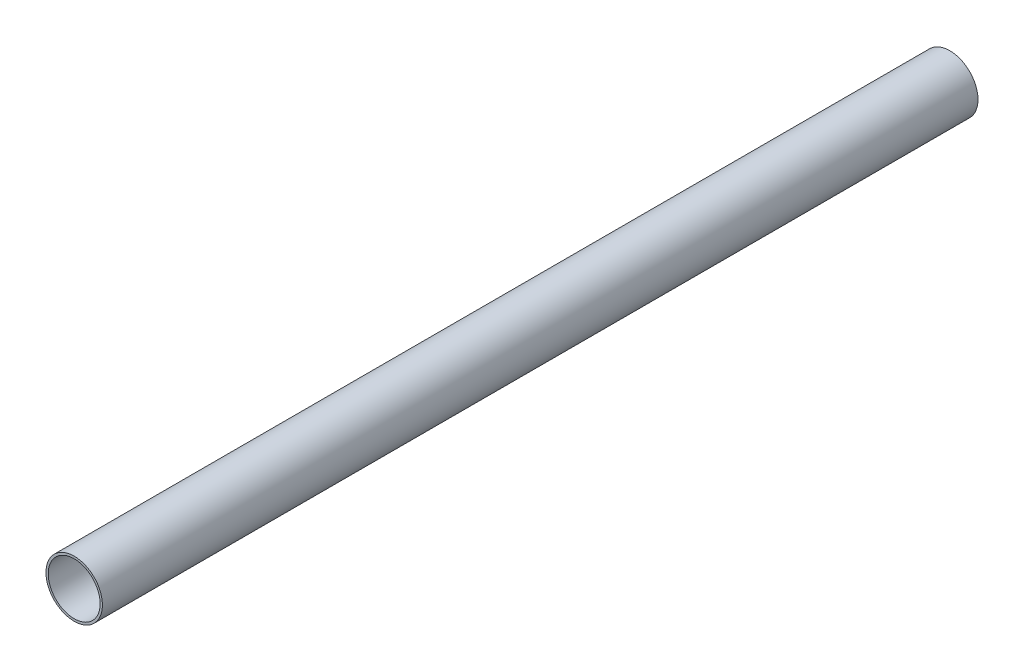
SolidWorks part; units mm, degrees
material "PC High Viscosity"
ref_plane "Front Plane" through (0, 0, 0) normal (0, 0, 1) x (1, 0, 0)
ref_plane "Top Plane" through (0, 0, 0) normal (0, 1, 0) x (1, 0, 0)
ref_plane "Right Plane" through (0, 0, 0) normal (1, 0, 0) x (0, 0, -1)
sketch "Sketch1" plane through (0, 0, 0) normal (0, 0, 1) x (1, 0, 0)
  circle A0 centre (0, 0) radius 12.5
  circle A1 centre (0, 0) radius 11.5
  dimension "D1" = 25
  dimension "D2" = 1
extrude "Boss-Extrude1" add sketch "Sketch1" along normal blind 387.62
